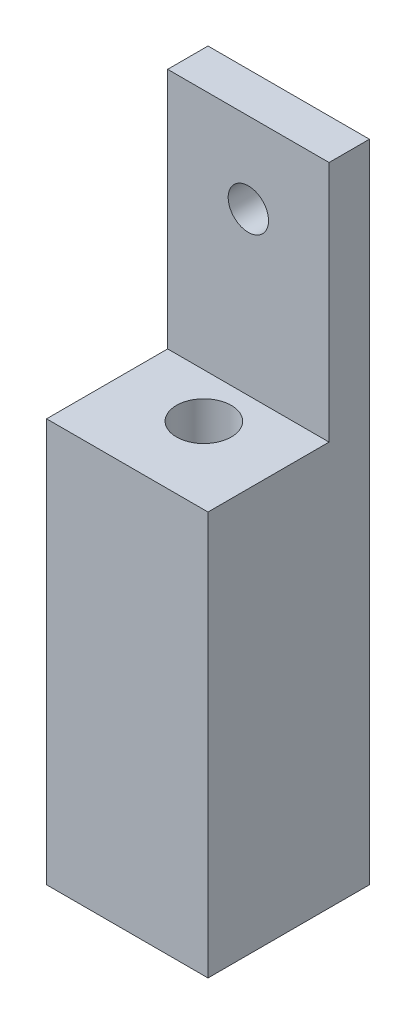
SolidWorks part; units mm, degrees
ref_plane "Front Plane" through (0, 0, 0) normal (0, 0, 1) x (1, 0, 0)
ref_plane "Top Plane" through (0, 0, 0) normal (0, 1, 0) x (1, 0, 0)
ref_plane "Right Plane" through (0, 0, 0) normal (1, 0, 0) x (0, 0, -1)
sketch "Sketch1" plane through (0, 0, 0) normal (0, 1, 0) x (1, 0, 0)
  line L1 (-10, -10) -> (10, -10)
  line L2 (-10, -10) -> (-10, 10)
  line L3 (-10, 10) -> (10, 10)
  line L4 (10, -10) -> (10, 10)
  line L5 (-10, -10) -> (10, 10) construction
  line L6 (-10, 10) -> (10, -10) construction
  circle A1 centre (0, -0.51) radius 3.4
  point P0 (0, 0)
  dimension "D1" = 6.8
  dimension "D2" = 20
  dimension "D3" = 0.51
extrude "Boss-Extrude1" add sketch "Sketch1" along normal mid plane 50
sketch "Sketch2" plane through (0, 25, 0) normal (0, 1, 0) x (1, 0, 0)
  line L0 (10, -10) -> (10, 10) construction
  line L1 (-10, 10) -> (10, 10)
  line L2 (-10, 10) -> (-10, 5)
  line L3 (-10, 5) -> (10, 5)
  line L4 (10, 10) -> (10, 5)
  dimension "D1" = 5
extrude "Boss-Extrude2" add sketch "Sketch2" along normal blind 30
sketch "Sketch3" plane through (0, 0, -5) normal (0, 0, 1) x (1, 0, 0)
  line L0 (0, 55) -> (0, 45) construction
  line L1 (-10, 55) -> (10, 55) construction
  line L2 (0, 45) -> (-10, 45) construction
  line L3 (-10, 55) -> (-10, 25) construction
  circle A0 centre (0, 45) radius 2.5
  dimension "D1" = 5
extrude "Cut-Extrude1" cut sketch "Sketch3" against normal through all
